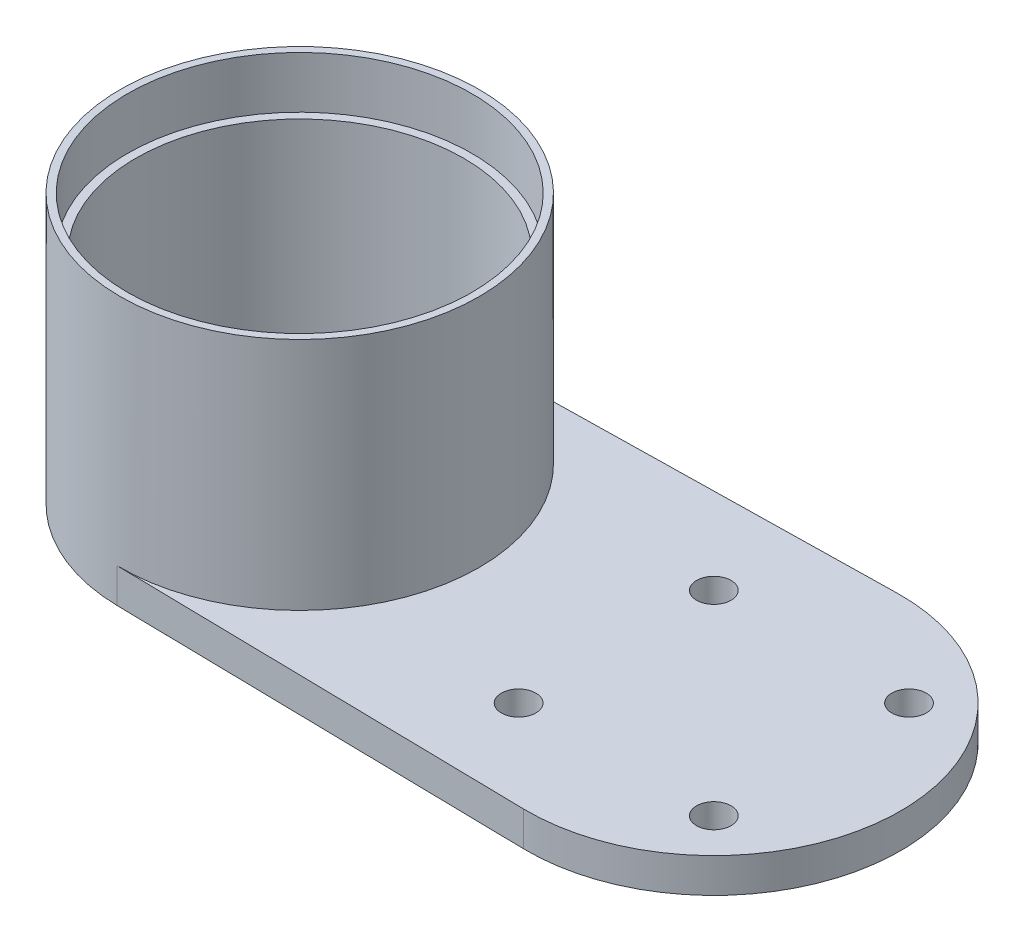
SolidWorks part; units mm, degrees
ref_plane "Front Plane" through (0, 0, 0) normal (0, 0, 1) x (1, 0, 0)
ref_plane "Top Plane" through (0, 0, 0) normal (0, 1, 0) x (1, 0, 0)
ref_plane "Right Plane" through (0, 0, 0) normal (1, 0, 0) x (0, 0, -1)
sketch "Sketch1" plane through (0, 0, 0) normal (0, 1, 0) x (1, 0, 0)
  circle A0 centre (0, 0) radius 26
  circle A1 centre (0, 0) radius 24.95
  dimension "D1" = 52
  dimension "D2" = 49.9
extrude "Boss-Extrude1" add sketch "Sketch1" along normal blind 7.5
sketch "Sketch2" plane through (0, 0, 0) normal (0, -1, 0) x (1, 0, 0)
  circle A0 centre (0, 0) radius 26
  circle A1 centre (0, 0) radius 23.75
  circle A2 centre (0, 0) radius 26 construction
  dimension "D1" = 47.5
extrude "Boss-Extrude2" add sketch "Sketch2" along normal blind 31.5
sketch "Sketch3" plane through (0, -31.5, 0) normal (0, -1, 0) x (1, 0, 0)
  circle A0 centre (0, 0) radius 23.75
  circle A1 centre (0, 0) radius 23.75 construction
extrude "Boss-Extrude3" add sketch "Sketch3" against normal blind 1
sketch "Sketch4" plane through (0, -31.5, 0) normal (0, -1, 0) x (1, 0, 0)
  circle A0 centre (0, 0) radius 3
  dimension "D1" = 6
extrude "Cut-Extrude1" cut sketch "Sketch4" against normal blind 1
sketch "Sketch5" plane through (0, -31.5, 0) normal (0, -1, 0) x (1, 0, 0)
  line L0 (-0.468, 25.9958) -> (59.5126, 27.0756)
  line L1 (59.5126, -27.0756) -> (-0.468, -25.9958)
  arc A0 (59.5126, -27.0756) -> (59.5126, 27.0756) centre (60, 0) ccw
  circle A1 centre (0, 0) radius 26 construction
  arc A2 (-0.468, 25.9958) -> (-0.468, -25.9958) centre (0, 0) cw
  dimension "D1" = 54.16
  dimension "D2" = 60
extrude "Boss-Extrude4" add sketch "Sketch5" against normal blind 5
sketch "Sketch6" plane through (0, -31.5, 0) normal (0, -1, 0) x (1, 0, 0)
  line L0 (40.8515, -19.1485) -> (79.1485, 19.1485) construction
  line L1 (40.8515, 19.1485) -> (79.1485, -19.1485) construction
  line L2 (60, 0) -> (0, 0) construction
  circle A0 centre (60, 0) radius 27.08 construction
  arc A1 (59.5126, -27.0756) -> (59.5126, 27.0756) centre (60, 0) ccw construction
  circle A2 centre (60, 0) radius 20 construction
  circle A3 centre (74.1421, 14.1421) radius 2.5
  circle A4 centre (74.1421, -14.1421) radius 2.5
  circle A5 centre (45.8579, -14.1421) radius 2.5
  circle A6 centre (45.8579, 14.1421) radius 2.5
  point P24 (60, 0)
  dimension "D3" = 40
  dimension "D4" = 5
  dimension "D1" = 90
  dimension "D2" = 45
  dimension "D5" = 4
extrude "Cut-Extrude2" cut sketch "Sketch6" against normal blind 5
